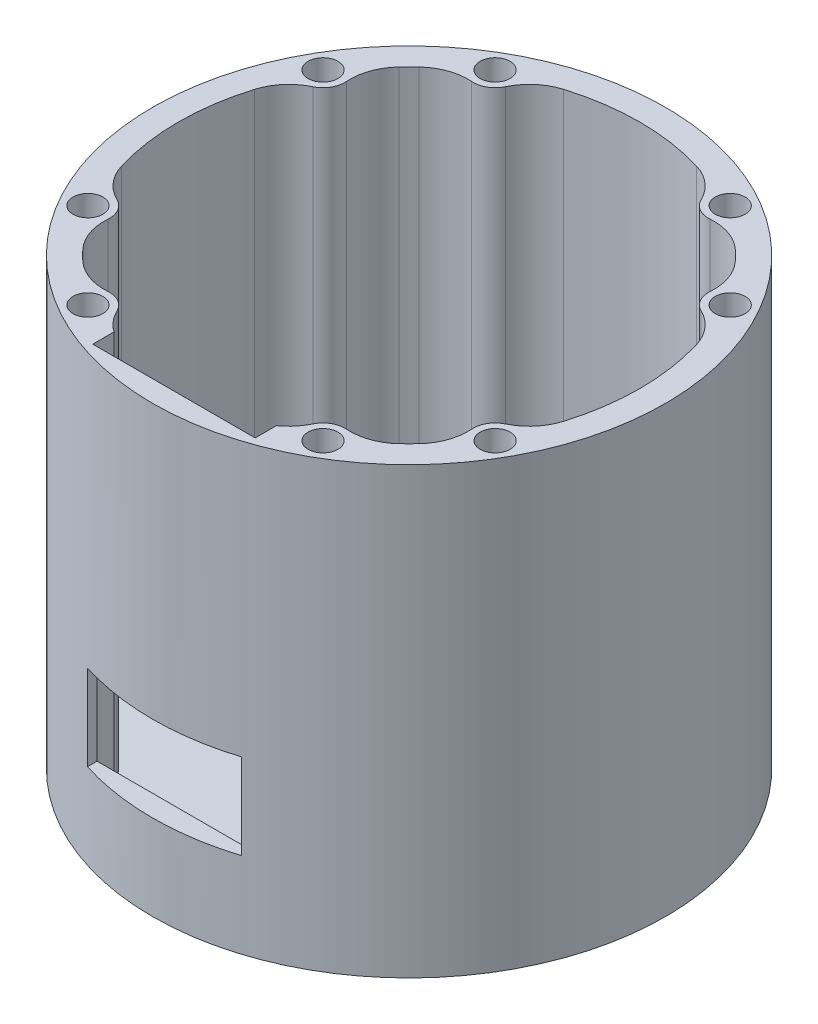
SolidWorks part; units mm, degrees
ref_plane "Ön Düzlem" through (0, 0, 0) normal (0, 0, 1) x (1, 0, 0)
ref_plane "Üst Düzlem" through (0, 0, 0) normal (0, 1, 0) x (1, 0, 0)
ref_plane "Sağ Düzlem" through (0, 0, 0) normal (1, 0, 0) x (0, 0, -1)
sketch "Sketch1" plane through (0, 0, 0) normal (0, 1, 0) x (1, 0, 0)
  circle A0 centre (0, 0) radius 30
  dimension "D1" = 60
extrude "Boss-Extrude1" add sketch "Sketch1" along normal blind 52
sketch "Sketch2" plane through (0, 52, 0) normal (0, 1, 0) x (1, 0, 0)
  line L23 (0, -35.176) -> (0, 35.176) construction
  line L24 (-35.1454, 0) -> (35.1454, 0) construction
  line L25 (0, 0) -> (-17.5855, 30.4589) construction
  arc A0 (-15.5866, 22.0467) -> (-22.0467, 15.5866) centre (0, 0) ccw
  arc A9 (-15.5866, 22.0467) -> (-11.2997, 24.5218) centre (-13.75, 23.8157) ccw
  arc A10 (-24.5218, 11.2997) -> (-22.0467, 15.5866) centre (-23.8157, 13.75) ccw
  arc A11 (-22.0467, -15.5866) -> (-24.5218, -11.2997) centre (-23.8157, -13.75) ccw
  arc A12 (-11.2997, -24.5218) -> (-15.5866, -22.0467) centre (-13.75, -23.8157) ccw
  arc A13 (15.5866, -22.0467) -> (11.2997, -24.5218) centre (13.75, -23.8157) ccw
  arc A14 (24.5218, -11.2997) -> (22.0467, -15.5866) centre (23.8157, -13.75) ccw
  arc A15 (22.0467, 15.5866) -> (24.5218, 11.2997) centre (23.8157, 13.75) ccw
  arc A16 (11.2997, 24.5218) -> (15.5866, 22.0467) centre (13.75, 23.8157) ccw
  arc A19 (-24.5218, 11.2997) -> (-24.5218, -11.2997) centre (0, 0) ccw
  arc A20 (-22.0467, -15.5866) -> (-15.5866, -22.0467) centre (0, 0) ccw
  arc A21 (15.5866, -22.0467) -> (22.0467, -15.5866) centre (0, 0) ccw
  arc A22 (-11.2997, -24.5218) -> (11.2997, -24.5218) centre (0, 0) ccw
  arc A23 (24.5218, -11.2997) -> (24.5218, 11.2997) centre (0, 0) ccw
  arc A24 (22.0467, 15.5866) -> (15.5866, 22.0467) centre (0, 0) ccw
  arc A25 (11.2997, 24.5218) -> (-11.2997, 24.5218) centre (0, 0) ccw
  point P8 (0, 0)
  point P13 (0, 0)
  point P17 (0, 0)
  point P30 (0, 0)
  dimension "D2" = 27.5
  dimension "D6" = 54
  dimension "D1" = 2.55
  dimension "D7" = 30
extrude "Cut-Extrude1" cut sketch "Sketch2" against normal blind 47
fillet "Fillet1" radius 6 16 edges at (-22.0467, 28.5, -15.5866) (-24.5218, 28.5, -11.2997) (-24.5218, 28.5, 11.2997) (-22.0467, 28.5, 15.5866) (-15.5866, 28.5, 22.0467) (-11.2997, 28.5, 24.5218) (11.2997, 28.5, 24.5218) (15.5866, 28.5, 22.0467) (22.0467, 28.5, 15.5866) (24.5218, 28.5, 11.2997) (24.5218, 28.5, -11.2997) (22.0467, 28.5, -15.5866) (15.5866, 28.5, -22.0467) (11.2997, 28.5, -24.5218) (-11.2997, 28.5, -24.5218) (-15.5866, 28.5, -22.0467)
sketch "Sketch4" plane through (0, 52, 0) normal (0, 1, 0) x (1, 0, 0)
  line L0 (-9.5, -27.5) -> (9.5, -27.5)
  line L1 (-9.5, -27.5) -> (-9.5, -24.5)
  line L2 (-9.5, -24.5) -> (9.5, -24.5)
  line L3 (9.5, -24.5) -> (9.5, -27.5)
  point P0 (0, -27.5)
  point P5 (0, -27.5)
  dimension "D1" = 27.5
  dimension "D2" = 19
  dimension "D3" = 3
extrude "Cut-Extrude3" cut sketch "Sketch4" against normal blind 45
sketch "Sketch6" plane through (0, 52, 0) normal (0, 1, 0) x (1, 0, 0)
  circle A0 centre (-13.75, 23.8157) radius 1.75
  circle A1 centre (-23.8157, 13.75) radius 1.75
  circle A2 centre (-23.8157, -13.75) radius 1.75
  circle A3 centre (-13.75, -23.8157) radius 1.75
  circle A4 centre (13.75, -23.8157) radius 1.75
  circle A5 centre (23.8157, -13.75) radius 1.75
  circle A6 centre (23.8157, 13.75) radius 1.75
  circle A7 centre (13.75, 23.8157) radius 1.75
  dimension "D1" = 3.5
extrude "Cut-Extrude4" cut sketch "Sketch6" against normal blind 5.5
sketch "Sketch7" plane through (0, 0, 0) normal (0, 0, 1) x (1, 0, 0)
  line L1 (-9, 10) -> (9, 10)
  line L2 (-9, 10) -> (-9, 20)
  line L3 (-9, 20) -> (9, 20)
  line L4 (9, 10) -> (9, 20)
  line L5 (-9, 10) -> (9, 20) construction
  line L6 (-9, 20) -> (9, 10) construction
  point P0 (0, 15)
  dimension "D1" = 18
  dimension "D2" = 10
  dimension "D3" = 10
extrude "Cut-Extrude5" cut sketch "Sketch7" along normal up to next
